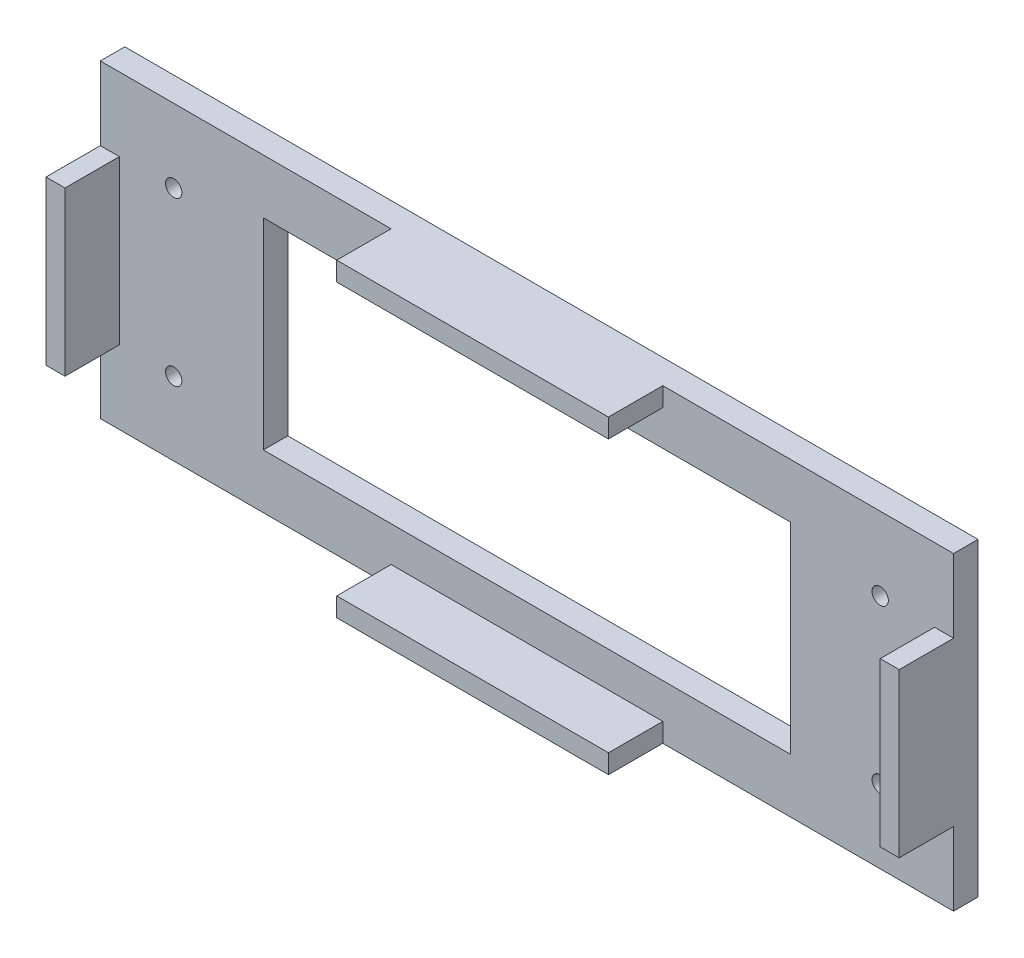
SolidWorks part; units mm, degrees
ref_plane "前视基准面" through (0, 0, 0) normal (0, 0, 1) x (1, 0, 0)
ref_plane "上视基准面" through (0, 0, 0) normal (0, 1, 0) x (1, 0, 0)
ref_plane "右视基准面" through (0, 0, 0) normal (1, 0, 0) x (0, 0, -1)
sketch "草图1" plane through (0, 0, 0) normal (0, 0, 1) x (1, 0, 0)
  line L0 (0, 109.6625) -> (0, -112.2549) construction
  line L1 (-156.0681, 0) -> (141.5501, 0) construction
  line L3 (-78.5, 28.5) -> (78.5, 28.5)
  line L4 (-78.5, 28.5) -> (-78.5, -28.5)
  line L5 (-78.5, -28.5) -> (78.5, -28.5)
  line L6 (78.5, 28.5) -> (78.5, -28.5)
  line L7 (-78.5, 28.5) -> (78.5, -28.5) construction
  line L8 (-78.5, -28.5) -> (78.5, 28.5) construction
  line L9 (-48.5, 18.5) -> (48.5, 18.5)
  line L10 (-48.5, 18.5) -> (-48.5, -18.5)
  line L11 (-48.5, -18.5) -> (48.5, -18.5)
  line L12 (48.5, 18.5) -> (48.5, -18.5)
  line L13 (-48.5, 18.5) -> (48.5, -18.5) construction
  line L14 (-48.5, -18.5) -> (48.5, 18.5) construction
  circle A0 centre (-65, 15) radius 1.5
  circle A1 centre (65, 15) radius 1.5
  circle A2 centre (-65, -15) radius 1.5
  circle A3 centre (65, -15) radius 1.5
  point P13 (0, 0)
  point P18 (0, 0)
  dimension "D1" = 130
  dimension "D2" = 30
  dimension "D3" = 3
  dimension "D4" = 157
  dimension "D5" = 57
  dimension "D6" = 10
  dimension "D7" = 30
extrude "凸台-拉伸1" add sketch "草图1" along normal blind 4.5
sketch "草图2" plane through (0, 0, 4.5) normal (0, 0, 1) x (1, 0, 0)
  line L0 (-99.8604, 0) -> (106.482, 0) construction
  line L1 (0, 52.1672) -> (0, -47.1563) construction
  line L2 (-78.5, 28.5) -> (-78.5, -28.5) construction
  line L3 (-75, -15) -> (-78.5, -15)
  line L4 (-75, -15) -> (-75, 15)
  line L5 (-75, 15) -> (-78.5, 15)
  line L6 (-78.5, -15) -> (-78.5, 15)
  line L7 (-75, -15) -> (-78.5, 15) construction
  line L8 (-75, 15) -> (-78.5, -15) construction
  line L9 (78.5, -28.5) -> (78.5, 28.5) construction
  line L10 (75, -15) -> (78.5, -15)
  line L11 (75, -15) -> (75, 15)
  line L12 (75, 15) -> (78.5, 15)
  line L13 (78.5, -15) -> (78.5, 15)
  line L14 (75, -15) -> (78.5, 15) construction
  line L15 (75, 15) -> (78.5, -15) construction
  line L16 (78.5, 28.5) -> (-78.5, 28.5) construction
  line L17 (-25, 25) -> (25, 25)
  line L18 (-25, 25) -> (-25, 28.5)
  line L19 (-25, 28.5) -> (25, 28.5)
  line L20 (25, 25) -> (25, 28.5)
  line L21 (-25, 25) -> (25, 28.5) construction
  line L22 (-25, 28.5) -> (25, 25) construction
  line L23 (-78.5, -28.5) -> (78.5, -28.5) construction
  line L24 (-25, -25) -> (25, -25)
  line L25 (-25, -25) -> (-25, -28.5)
  line L26 (-25, -28.5) -> (25, -28.5)
  line L27 (25, -25) -> (25, -28.5)
  line L28 (-25, -25) -> (25, -28.5) construction
  line L29 (-25, -28.5) -> (25, -25) construction
  point P5 (-76.75, 0)
  point P12 (76.75, 0)
  point P19 (0, 26.75)
  point P26 (0, -26.75)
  dimension "D1" = 50
  dimension "D2" = 150
  dimension "D3" = 30
  dimension "D4" = 50
extrude "凸台-拉伸2" add sketch "草图2" along normal blind 10
